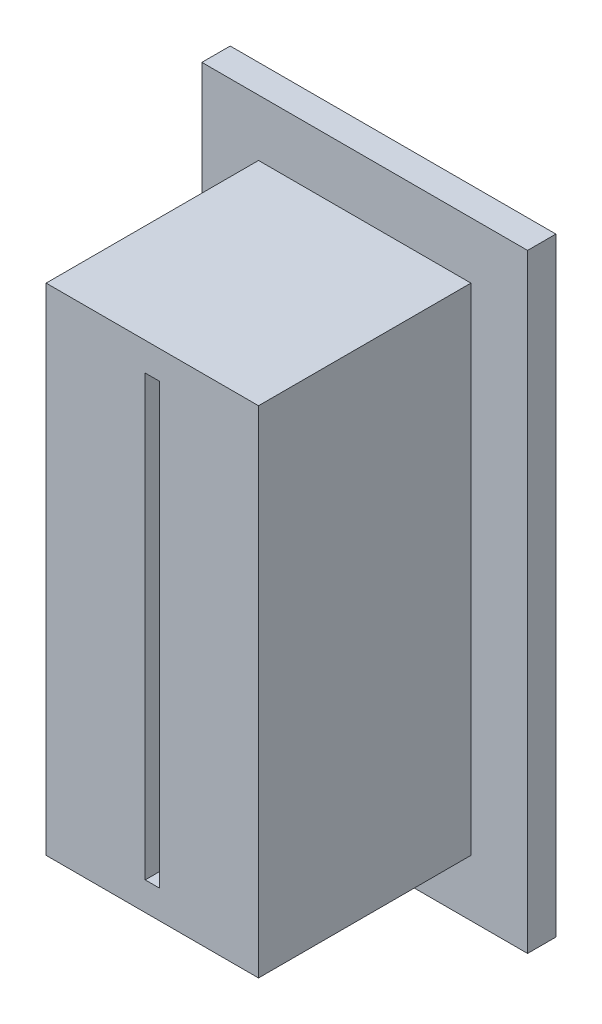
SolidWorks part; units mm, degrees
ref_plane "Front Plane" through (0, 0, 0) normal (0, 0, 1) x (1, 0, 0)
ref_plane "Top Plane" through (0, 0, 0) normal (0, 1, 0) x (1, 0, 0)
ref_plane "Right Plane" through (0, 0, 0) normal (1, 0, 0) x (0, 0, -1)
sketch "Sketch1" plane through (0, 0, 0) normal (0, 0, 1) x (1, 0, 0)
  line L1 (-7.5, 17.5) -> (7.5, 17.5)
  line L2 (-7.5, 17.5) -> (-7.5, -17.5)
  line L3 (-7.5, -17.5) -> (7.5, -17.5)
  line L4 (7.5, 17.5) -> (7.5, -17.5)
  point P4 (0, -17.5)
  point P6 (-7.5, 0)
  dimension "D1" = 15
  dimension "D2" = 35
extrude "Boss-Extrude1" add sketch "Sketch1" along normal blind 15
sketch "Sketch3" plane through (0, 0, 0) normal (0, 0, -1) x (-1, 0, 0)
  line L8 (6, -16) -> (6, 16)
  line L9 (6, 16) -> (-6, 16)
  line L10 (-6, 16) -> (-6, -16)
  line L11 (-6, -16) -> (6, -16)
  line L12 (6, -16) -> (6, 16)
  line L13 (6, 16) -> (-6, 16)
  line L14 (-6, 16) -> (-6, -16)
  line L15 (-6, -16) -> (6, -16)
  dimension "D1" = 1.5
extrude "Cut-Extrude2" cut sketch "Sketch3" against normal offset from surface (13.5 mm away) 1.5 up to face at (0, 0, 15)
sketch "Sketch4" plane through (0, 0, 0) normal (0, 0, -1) x (-1, 0, 0)
  line L10 (-6, -16) -> (6, -16) construction
  line L11 (-6, -16) -> (6, -16)
  line L12 (6, 16) -> (-6, 16) construction
  line L13 (-6, 16) -> (-6, -16) construction
  line L14 (11.5, 21.5) -> (-11.5, 21.5)
  line L15 (-11.5, 21.5) -> (-11.5, -21.5)
  line L16 (11.5, -21.5) -> (11.5, 21.5)
  line L17 (-11.5, -21.5) -> (11.5, -21.5)
  line L18 (11.5, 21.5) -> (-11.5, 21.5)
  line L19 (-11.5, 21.5) -> (-11.5, -21.5)
  line L20 (11.5, -21.5) -> (11.5, 21.5)
  line L21 (-11.5, -21.5) -> (11.5, -21.5)
  line L22 (6, -16) -> (6, 16) construction
  line L23 (6, 16) -> (-6, 16)
  line L24 (-6, 16) -> (-6, -16)
  line L25 (6, -16) -> (6, 16)
  dimension "D1" = 4
extrude "Boss-Extrude2" add sketch "Sketch4" along normal blind 2
sketch "Sketch5" plane through (0, 0, 15) normal (0, 0, 1) x (1, 0, 0)
  line L0 (7.5, 17.5) -> (-7.5, 17.5) construction
  line L1 (0.5, -15.5) -> (-0.5, -15.5)
  line L2 (0.5, -15.5) -> (0.5, 15.5)
  line L3 (0.5, 15.5) -> (-0.5, 15.5)
  line L4 (-0.5, -15.5) -> (-0.5, 15.5)
  point P4 (0.5, 0)
  point P6 (0, 15.5)
  dimension "D1" = 2
  dimension "D2" = 1
extrude "Cut-Extrude3" cut sketch "Sketch5" against normal blind 2
